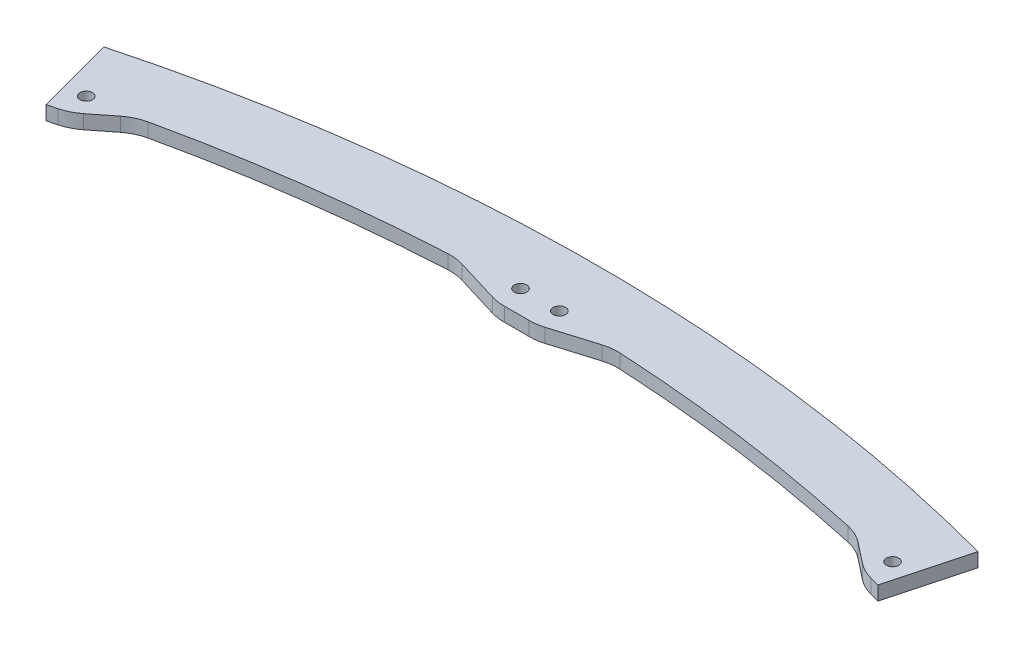
SolidWorks part; units mm, degrees
ref_plane "Front Plane" through (0, 0, 0) normal (0, 0, 1) x (1, 0, 0)
ref_plane "Top Plane" through (0, 0, 0) normal (0, 1, 0) x (1, 0, 0)
ref_plane "Right Plane" through (0, 0, 0) normal (1, 0, 0) x (0, 0, -1)
sketch "Sketch1" plane through (0, 0, 0) normal (0, 1, 0) x (1, 0, 0)
  line L0 (0, 0) -> (-280.8187, 1048.0295)
  line L1 (-280.8187, 1085) -> (280.8187, 1085) construction
  line L2 (-280.8187, 1085) -> (-280.8187, 785) construction
  line L3 (-280.8187, 785) -> (280.8187, 785) construction
  line L4 (280.8187, 1085) -> (280.8187, 785) construction
  line L5 (0, 0) -> (280.8187, 1048.0295)
  line L6 (0, 1020) -> (0, 0) construction
  line L7 (-12.5, 1032.4243) -> (-50, 1043.8031)
  line L8 (12.5, 1032.4243) -> (50, 1043.8031)
  line L9 (955, 0) -> (1000, 0) construction
  line L10 (1000, 0) -> (1045, 0) construction
  line L11 (-255.137, 1000.4806) -> (-231.6307, 1019.0055)
  line L12 (255.137, 1000.4806) -> (231.6307, 1019.0055)
  circle A0 centre (0, 0) radius 1085
  circle A1 centre (0, 0) radius 1045
  circle A2 centre (0, 0) radius 955
  circle A3 centre (0, 0) radius 915
  circle A6 centre (0, 0) radius 1065 construction
  circle A7 centre (0, 0) radius 935 construction
  circle A9 centre (-227.4758, 906.9067) radius 4
  circle A10 centre (227.4758, 906.9067) radius 4
  circle A12 centre (0, 0) radius 1032.5 construction
  arc A13 (-12.5, 1032.4243) -> (12.5, 1032.4243) centre (0, 0) cw
  circle A14 centre (-12.5, 1047.4254) radius 4
  circle A15 centre (0, 0) radius 1000 construction
  circle A16 centre (12.5, 1047.4254) radius 4
  arc A17 (-255.137, 1000.4806) -> (-267.2307, 997.3184) centre (0, 0) ccw
  circle A18 centre (-259.0196, 1014.9705) radius 4
  arc A19 (-255.137, 1000.4806) -> (-261.0384, 989.4611) centre (-1168.263, 1482.4113) cw
  arc A21 (255.137, 1000.4806) -> (267.2307, 997.3184) centre (0, 0) cw
  circle A22 centre (259.0196, 1014.9705) radius 4
  point P12 (0, 785)
  dimension "D3" = 40
  dimension "D4" = 40
  dimension "D5" = 20
  dimension "D6" = 20
  dimension "D7" = 170
  dimension "D8" = 2000
  dimension "D9" = 40
  dimension "D11" = 8
  dimension "D12" = 15
  dimension "D14" = 12.5
  dimension "D15" = 12.5
  dimension "D19" = 8
  dimension "D20" = 12.5
  dimension "D21" = 1047.5
  dimension "D22" = 12.5
  dimension "D23" = 12.5
  dimension "D10" = 8
  dimension "D24" = 1047.5
  dimension "D1" = 300
  dimension "D2" = 15
  dimension "D13" = 15
  dimension "D16" = 12.5
  dimension "D17" = 50
  dimension "D18" = 50
extrude "Boss-Extrude1" add sketch "Sketch1" along normal blind 9 contours L5 A6 L0 A1 | L7 A13 L8 A1 | A18 A1 L0 A17 L11 | A1 A22 L12 A21 L5
fillet "Fillet1" radius 30 8 edges at (50, 4.5, -1043.8031) (-50, 4.5, -1043.8031) (-12.5, 4.5, -1032.4243) (12.5, 4.5, -1032.4243) (255.137, 4.5, -1000.4806) (231.6307, 4.5, -1019.0055) (-255.137, 4.5, -1000.4806) (-231.6307, 4.5, -1019.0055)
